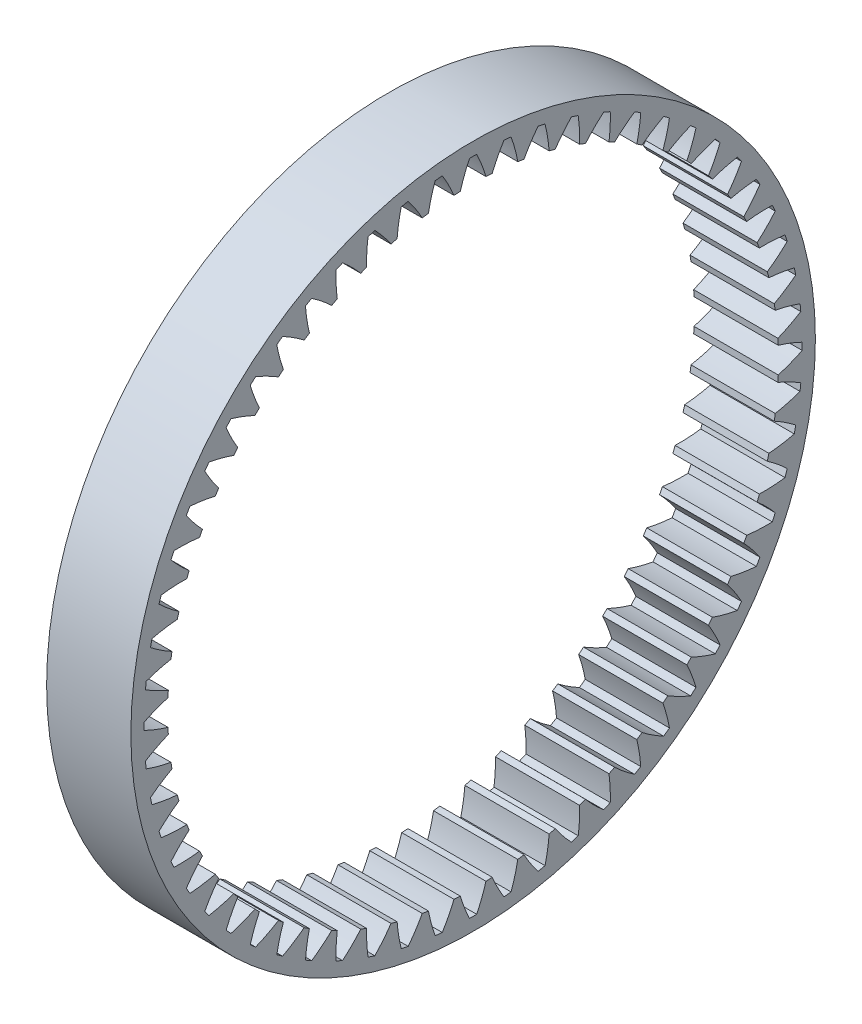
SolidWorks part; units mm, degrees
ref_plane "Plane1" through (0, 0, 0) normal (0, 0, 1) x (1, 0, 0)
ref_plane "Plane2" through (0, 0, 0) normal (0, 1, 0) x (1, 0, 0)
ref_plane "Plane3" through (0, 0, 0) normal (1, 0, 0) x (0, 0, -1)
other "Configuration Table"
sketch "HoldingSke" plane through (0, 0, 0) normal (0, 1, 0) x (1, 0, 0)
  line L0 (0, 0) -> (0.5, -0.866)
  line L1 (-15, 0) -> (100, 0) construction
  line L2 (0, 0) -> (-2.1039, 2.3779)
  line L3 (0, 0) -> (-11.863, 4.5341)
  line L4 (0, 0) -> (4.318, 7.479)
  line L5 (0, 0) -> (-23.7986, -8.8762)
  line L6 (0, 0) -> (-10.5278, -7.1032)
  line L7 (-2.1039, 2.3779) -> (3.3635, 27.1825)
  line L8 (-76.2, 3.3779) -> (-54.61, 3.3779)
  line L9 (-71.009, 38.7566) -> (-53.1078, 45.2721)
  line L10 (-76.2, 71.12) -> (104.1128, 71.12)
  line L11 (0, 0) -> (-8, 0)
  line L12 (-76.2, 101.6) -> (-76.162, 101.6)
  line L13 (24.9733, 27.94) -> (52.9518, 28.4284)
  line L14 (24.9733, 27.94) -> (24.9743, 27.94)
  line L15 (24.9733, 27.94) -> (100.4006, 29.5858)
  circle A0 centre (0, 0) radius 32.5
  circle A1 centre (0, 0) radius 12.7
  circle A2 centre (0, 0) radius 12.7
  dimension "MHD" = 25.4
  dimension "Hub_dia" = 25.4
  dimension "Diameter" = 65
  dimension "Num_teeth" = 60
  dimension "Pitch" = 1
  dimension "Overall_len" = 25.4
  dimension "Show_teeth" = 60
  dimension "Thickness" = 12.7
  dimension "OAL" = 25.4001
  dimension "T_dim" = 21.59
  dimension "Ap" = 20
  dimension "H" = 19.05
  dimension "Pitch_radius" = 180.3128
  dimension "Width" = 8
  dimension "Backlash" = 0.038
  dimension "Addendum_fac" = 1
  dimension "Dedendum_fac" = 1.25
  dimension "Clearance_fac" = 0.25
  dimension "Dedendum_add" = 0.001
  dimension "Module" = 1
sketch "BasProSke" plane through (0, 0, 0) normal (0, 1, 0) x (1, 0, 0)
  line L0 (-10, 0) -> (60, 0) construction
  line L1 (0, 29) -> (0, 32.5)
  line L2 (0, 29) -> (8, 29)
  line L3 (8, 29) -> (8, 32.5)
  line L4 (8, 32.5) -> (0, 32.5)
  dimension "Diameter" = 65
  dimension "Thickness" = 8
  dimension "Inside_diameter" = 58
revolve "Base-Revolve" add sketch "BasProSke" angle 360 about L0
sketch "TooCutSke" plane through (0, 0, 0) normal (1, 0, 0) x (0, 0, -1)
  line L3 (0.8803, 29.9871) -> (0.8803, 53.6633) construction
  line L4 (0, 0) -> (0, 59.563) construction
  line L5 (0, 0) -> (-3.576, 68.2339) construction
  line L6 (-13.1633, 24.7167) -> (36.4631, 27.3175) construction
  circle A0 centre (0, 0) radius 30 construction
  circle A1 centre (0, 0) radius 31.251 construction
  circle A2 centre (0, 0) radius 25.3717 construction
  circle A3 centre (0, 0) radius 28.9746 construction
  arc A4 (1.2274, 28.9486) -> (0.3395, 31.2492) centre (-13.1633, 24.7167) ccw
  arc A5 (1.2274, 28.9486) -> (-1.2274, 28.9486) centre (0, 0) ccw
  arc A6 (0.3395, 31.2492) -> (-0.3395, 31.2492) centre (0, 0) ccw
  arc A7 (-0.3395, 31.2492) -> (-1.2274, 28.9486) centre (13.1633, 24.7167) ccw
  dimension "Pitch_dia" = 60
  dimension "Base_dia" = 50.7434
  dimension "Root_dia" = 62.502
  dimension "Overcut_dia" = 57.9492
  dimension "Flank_rad" = 15
  dimension "Half_ang" = 3
  dimension "Half_CT" = 0.8803
extrude "ToothCut" cut sketch "TooCutSke" along normal through all
fillet "Breaks" [suppressed] radius 0.1
fillet "RootFillets" [suppressed] radius 0.251
pattern_circular "TeethCuts" count 60 every 6 about axis through (-10, 0, 0) along (1, 0, 0) of "RootFillets", "Breaks", "ToothCut"
equation "' \"Module@HoldingSke\" = 6.35"
equation "' \"Num_teeth@HoldingSke\" = 24"
equation "' \"Ap@HoldingSke\" =  14.5"
equation "' \"Ap@HoldingSke\" = 14.5"
equation "' \"Width@HoldingSke\" = 12"
equation "' \"Diameter@HoldingSke\" = 8 * 25.4"
equation "' \"Show_teeth@HoldingSke\" = 100"
equation "' \"Backlash@HoldingSke\" = 0.009 * 25.4"
equation "' \"Addendum_fac@HoldingSke\" = 1.0"
equation "' \"Dedendum_fac@HoldingSke\" = 1.25"
equation "' \"Dedendum_add@HoldingSke\" = 0.00005 * 25.4"
equation "' \"Clearance_fac@HoldingSke\" = 0.25"
equation "\"Pitch@HoldingSke\" = 1 / \"Module@HoldingSke\" "
equation "\"Overcut_dia@TooCutSke\" = (\"Num_teeth@HoldingSke\" - 2 * \"Addendum_fac@HoldingSke\") / \"Pitch@HoldingSke\" - 0.002 * 25.4"
equation "\"Pitch_dia@TooCutSke\" = \"Num_teeth@HoldingSke\" / \"Pitch@HoldingSke\""
equation "\"Base_dia@TooCutSke\" = \"Num_teeth@HoldingSke\" / \"Pitch@HoldingSke\" * cos((\"Ap@HoldingSke\"  * 3.14159265 / 180)) * 0.90"
equation "\"Root_dia@TooCutSke\" = \"Num_teeth@HoldingSke\"  / \"Pitch@HoldingSke\" + 2 *  \"Dedendum_fac@HoldingSke\"/ \"Pitch@HoldingSke\" + \"Dedendum_add@HoldingSke\" * 2"
equation "\"Half_ang@TooCutSke\" = 180 / \"Num_teeth@HoldingSke\""
equation "\"Half_CT@TooCutSke\" = \"Num_teeth@HoldingSke\" / \"Pitch@HoldingSke\" * sin((3.14159265 / 2 / \"Num_teeth@HoldingSke\")) / 2 + 10 * \"Backlash@HoldingSke\" / 4"
equation "\"Flank_rad@TooCutSke\" = \"Num_teeth@HoldingSke\" / \"Pitch@HoldingSke\" / 4"
equation "\"Radius@RootFillets\"= \"Clearance_fac@HoldingSke\" / \"Pitch@HoldingSke\" + \"Dedendum_add@HoldingSke\""
equation "\"Break_rad@Breaks\" = 0.02 / \"Pitch@HoldingSke\" * 5"
equation "\"Num_teeth@TeethCuts\" = int( \"Show_teeth@HoldingSke\" ) + 1"
equation "\"Num_teeth@TeethCuts\" = ((sgn( \"Num_teeth@TeethCuts\" - \"Num_teeth@HoldingSke\" )-1)*( \"Num_teeth@TeethCuts\" - \"Num_teeth@HoldingSke\" ))/-2+ \"Num_teeth@HoldingSke\""
equation "\"Num_teeth@TeethCuts\" = ((sgn( \"Num_teeth@TeethCuts\" - 2.0)+1)*( \"Num_teeth@TeethCuts\" - 2.0))/2 +2.0"
equation "\"Angle@TeethCuts\" = 360.0 / \"Num_teeth@HoldingSke\""
equation "\"Diameter@BasProSke\" = \"Num_teeth@HoldingSke\"  / \"Pitch@HoldingSke\" + 2 *  \"Dedendum_fac@HoldingSke\"/ \"Pitch@HoldingSke\" + \"Dedendum_add@HoldingSke\" * 2 + 0.002 * 25.4"
equation "\"Diameter@BasProSke\" = ((sgn( \"Diameter@BasProSke\"  - \"Diameter@HoldingSke\" )+1)*( \"Diameter@BasProSke\"  - \"Diameter@HoldingSke\" ))/2 + \"Diameter@HoldingSke\""
equation "\"Inside_diameter@BasProSke\" =  (\"Num_teeth@HoldingSke\" - 2 * \"Addendum_fac@HoldingSke\") / \"Pitch@HoldingSke\" "
equation "\"Thickness@BasProSke\"  = \"Width@HoldingSke\""
